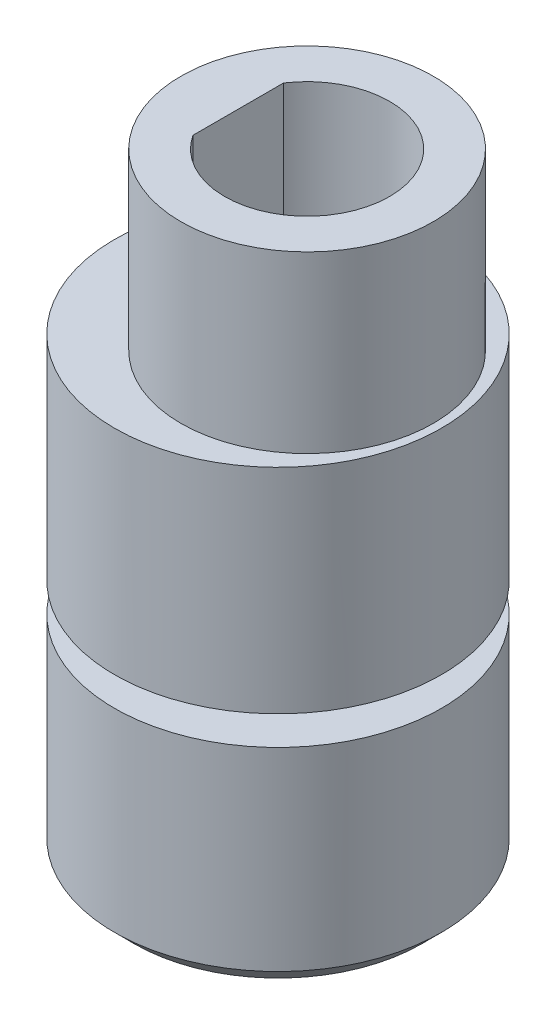
SolidWorks part; units mm, degrees
ref_plane "Front Plane" through (0, 0, 0) normal (0, 0, 1) x (1, 0, 0)
ref_plane "Top Plane" through (0, 0, 0) normal (0, 1, 0) x (1, 0, 0)
ref_plane "Right Plane" through (0, 0, 0) normal (1, 0, 0) x (0, 0, -1)
sketch "Sketch1" plane through (0, 0, 0) normal (0, 1, 0) x (1, 0, 0)
  circle A0 centre (0, 0) radius 8.425
  dimension "D1" = 16.85
extrude "Boss-Extrude1" add sketch "Sketch1" along normal blind 11
sketch "Sketch3" plane through (0, 0, 0) normal (0, -1, 0) x (1, 0, 0)
  line L0 (0, 0) -> (1.5, 0) construction
  line L1 (1.5, 0) -> (1.5, 1.5) construction
  circle A0 centre (1.5, 1.5) radius 8.425
  dimension "D1" = 16.85
  dimension "D3" = 1.5
  dimension "D4" = 1.5
extrude "Boss-Extrude2" add sketch "Sketch3" along normal blind 11
sketch "Sketch4" plane through (0, -11, 0) normal (0, -1, 0) x (1, 0, 0)
  line L0 (0, 0) -> (1.5, 0) construction
  circle A0 centre (1.5, 0) radius 4.25
  dimension "D2" = 8.5
  dimension "D1" = 1.5
extrude "Cut-Extrude1" cut sketch "Sketch4" against normal through all
sketch "Sketch5" plane through (0, -11, 0) normal (0, -1, 0) x (1, 0, 0)
  line L0 (1.5, 0) -> (-2.75, 0) construction
  line L1 (-2.05, 2.3367) -> (-2.05, -2.3367)
  circle A0 centre (1.5, 0) radius 4.25 construction
  arc A1 (-2.05, 2.3367) -> (-2.05, -2.3367) centre (1.5, 0) ccw
  dimension "D1" = 0.7
extrude "Boss-Extrude3" add sketch "Sketch5" against normal up to surface (22 mm away) up to face at (1.5, 11, -4.25)
chamfer "Chamfer1" distance 1 angle 45 1 edges at (1.5, -11, -6.925)
sketch "Sketch6" plane through (0, 11, 0) normal (0, 1, 0) x (1, 0, 0)
  line L0 (-2.05, 2.3367) -> (-2.05, -2.3367) construction
  line L1 (-2.05, 2.3367) -> (-2.05, -2.3367)
  circle A0 centre (1.5, 0) radius 6.5
  arc A1 (-2.05, -2.3367) -> (-2.05, 2.3367) centre (1.5, 0) ccw construction
  arc A2 (-2.05, -2.3367) -> (-2.05, 2.3367) centre (1.5, 0) ccw
  dimension "D1" = 13
extrude "Boss-Extrude4" add sketch "Sketch6" along normal blind 9
sketch "Sketch7" plane through (0, -11, 0) normal (0, -1, 0) x (1, 0, 0)
  line L0 (-2.05, -2.3367) -> (-2.05, 2.3367) construction
  line L1 (-2.05, -2.3367) -> (-2.05, 2.3367)
  arc A0 (-2.05, -2.3367) -> (-2.05, 2.3367) centre (1.5, 0) ccw construction
  arc A1 (-2.05, -2.3367) -> (-2.05, 2.3367) centre (1.5, 0) ccw
extrude "Boss-Extrude5" add sketch "Sketch7" against normal blind 8
sketch "Sketch10" plane through (0, -11, 0) normal (0, -1, 0) x (1, 0, 0)
  circle A0 centre (1.5345, 0) radius 1.1041
extrude "Cut-Extrude2" cut sketch "Sketch10" against normal through all
